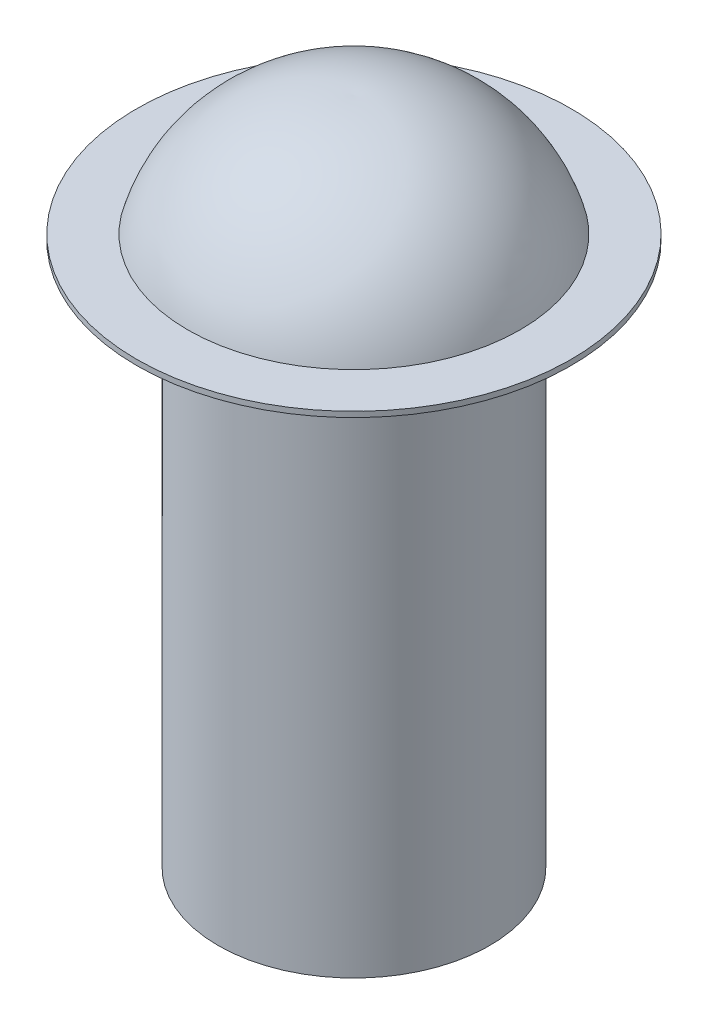
SolidWorks part; units mm, degrees
ref_plane "Front Plane" through (0, 0, 0) normal (0, 0, 1) x (1, 0, 0)
ref_plane "Top Plane" through (0, 0, 0) normal (0, 1, 0) x (1, 0, 0)
ref_plane "Right Plane" through (0, 0, 0) normal (1, 0, 0) x (0, 0, -1)
sketch "Sketch1" plane through (0, 0, 0) normal (0, 1, 0) x (1, 0, 0)
  circle A0 centre (0, 0) radius 3.175
  dimension "D1" = 6.35
extrude "Boss-Extrude1" add sketch "Sketch1" along normal blind 12.7
sketch "Sketch2" plane through (0, 12.7, 0) normal (0, 1, 0) x (1, 0, 0)
  circle A0 centre (0, 0) radius 5.08
  circle A1 centre (0, 0) radius 3.175 construction
  dimension "D1" = 10.16
extrude "Boss-Extrude2" add sketch "Sketch2" along normal blind 0.127
sketch "Sketch3" plane through (0, 0, 0) normal (0, 0, 1) x (1, 0, 0)
  line L0 (0, 12.827) -> (-3.8863, 12.827)
  line L1 (5.08, 12.827) -> (-5.08, 12.827) construction
  line L2 (0, 12.827) -> (0, 15.6476)
  arc A0 (-3.8863, 12.827) -> (0, 15.6476) centre (-0.1666, 11.7894) cw
  dimension "D1" = 3.8618
  dimension "D2" = 0.1666
  dimension "D3" = 3.8863
revolve "Revolve1" add sketch "Sketch3" angle 360 about L2
